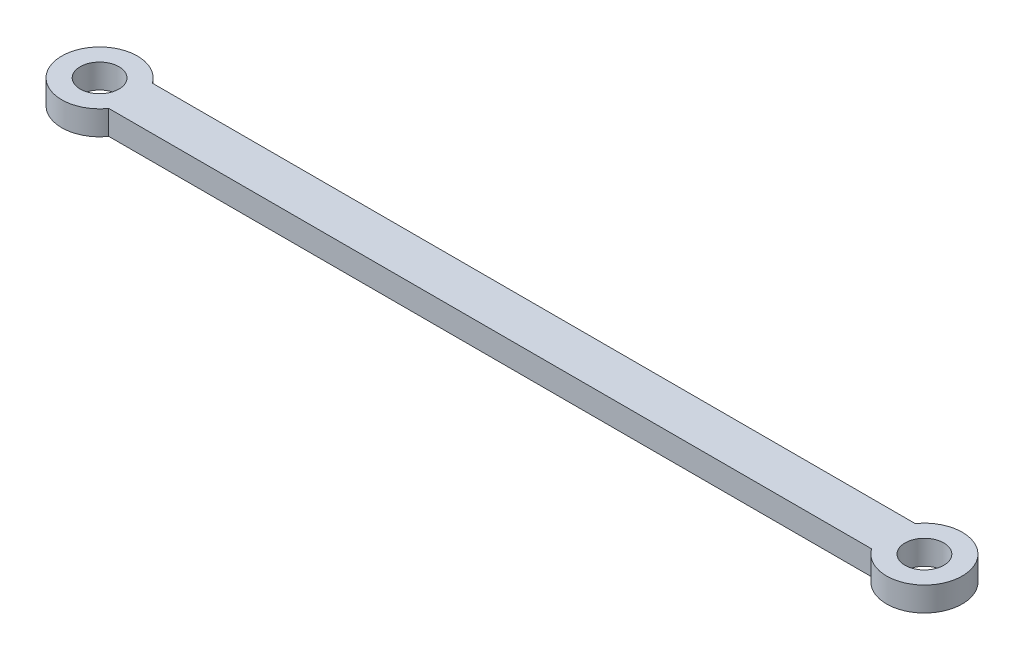
SolidWorks part; units mm, degrees
material "Acrylic (Medium-high impact)"
ref_plane "Front Plane" through (0, 0, 0) normal (0, 0, 1) x (1, 0, 0)
ref_plane "Top Plane" through (0, 0, 0) normal (0, 1, 0) x (1, 0, 0)
ref_plane "Right Plane" through (0, 0, 0) normal (1, 0, 0) x (0, 0, -1)
sketch "Sketch1" plane through (0, 0, 0) normal (0, 1, 0) x (1, 0, 0)
  line L0 (0, 0) -> (78.3381, 0) construction
  line L1 (0, 0) -> (0, 51263.8953) construction
  line L2 (-78.6164, -4.5) -> (78.6164, -4.5)
  line L3 (-78.6164, 4.5) -> (78.6164, 4.5)
  circle A0 centre (85, 0) radius 4
  arc A1 (78.6164, -4.5) -> (78.6164, 4.5) centre (85, 0) ccw
  arc A2 (-78.6164, -4.5) -> (-78.6164, 4.5) centre (-85, 0) cw
  circle A3 centre (-85, 0) radius 4
  point P10 (0, -4.5)
  point P17 (0, 4.5)
  dimension "D2" = 8
  dimension "D1" = 7.8102
  dimension "D3" = 4.5
  dimension "D4" = 85
extrude "Boss-Extrude1" add sketch "Sketch1" along normal blind 5
